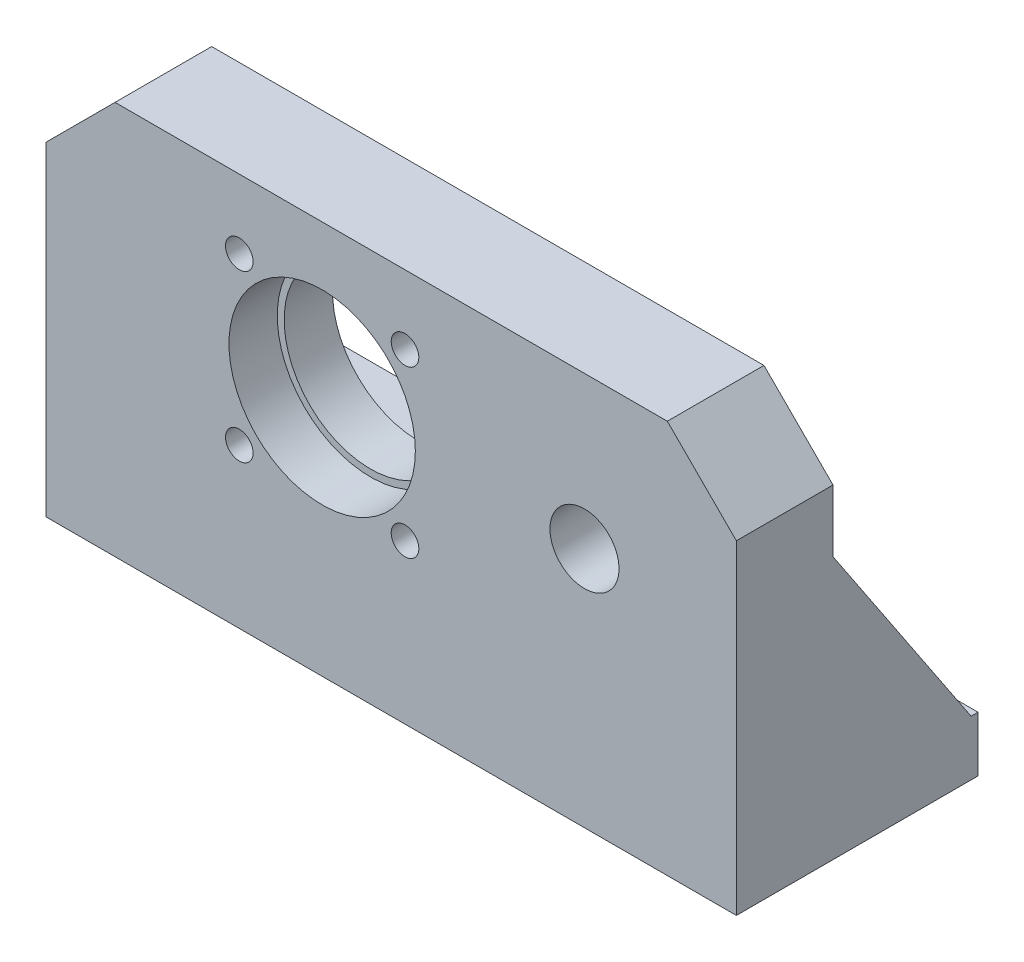
SolidWorks part; units mm, degrees
ref_plane "Front Plane" through (0, 0, 0) normal (0, 0, 1) x (1, 0, 0)
ref_plane "Top Plane" through (0, 0, 0) normal (0, 1, 0) x (1, 0, 0)
ref_plane "Right Plane" through (0, 0, 0) normal (1, 0, 0) x (0, 0, -1)
sketch "Sketch1" plane through (0, 0, 0) normal (0, 0, 1) x (1, 0, 0)
  line L0 (-40, -8) -> (-40, -35)
  line L1 (-40, -35) -> (60, -35)
  line L2 (60, -35) -> (60, 3.08)
  line L3 (60, 3.08) -> (60, 22)
  line L4 (60, 22) -> (-40, 22)
  line L5 (-40, 22) -> (-40, -8)
  circle A0 centre (0, 0) radius 13.5
  dimension "D1" = 27
  dimension "D2" = 100
  dimension "D3" = 35
  dimension "D4" = 57
  dimension "D5" = 60
extrude "Boss-Extrude1" add sketch "Sketch1" along normal blind 14
sketch "Sketch2" plane through (0, 0, 14) normal (0, 0, 1) x (1, 0, 0)
  circle A0 centre (0, 0) radius 13.5
  circle A1 centre (0, 0) radius 12.5
extrude "Boss-Extrude2" add sketch "Sketch2" against normal blind 7
sketch "Sketch11" plane through (0, 0, 14) normal (0, 0, 1) x (1, 0, 0)
  line L5 (-12, -12) -> (12, -12) construction
  line L6 (-12, -12) -> (-12, 12) construction
  line L7 (-12, 12) -> (12, 12) construction
  line L8 (12, -12) -> (12, 12) construction
  line L9 (-12, -12) -> (12, 12) construction
  line L10 (-12, 12) -> (12, -12) construction
  point P0 (0, 0)
sketch "Sketch16" plane through (0, -35, 0) normal (0, -1, 0) x (1, 0, 0)
  line L0 (60, 14) -> (60, 0) construction
  line L1 (-40, 0) -> (60, 0)
  line L2 (-40, 0) -> (-40, 35)
  line L3 (-40, 35) -> (60, 35)
  line L4 (60, 0) -> (60, 35)
  dimension "D1" = 35
extrude "Boss-Extrude3" add sketch "Sketch16" against normal blind 8
sketch "Sketch17" plane through (60, 0, 0) normal (1, 0, 0) x (0, 0, -1)
  line L0 (-34, -27) -> (-14, 3)
  line L1 (-14, -27) -> (-14, 22) construction
  line L2 (-34, -27) -> (-14, -27)
  line L3 (-14, -27) -> (-14, 3)
  line L5 (-14, -27) -> (-35, -27) construction
  dimension "D1" = 20
  dimension "D2" = 30
extrude "Boss-Extrude4" add sketch "Sketch17" against normal blind 8
ref_plane "Plane1" through (10, 0, 0) normal (1, 0, 0) x (0, 0, -1)
mirror "Mirror1" about plane through (10, 0, 0) normal (1, 0, 0) of "Boss-Extrude4"
sketch "Sketch19" plane through (0, 0, 35) normal (0, 0, 1) x (1, 0, 0)
  line L1 (60, -27) -> (16, -27)
  line L2 (60, -27) -> (60, 22)
  line L3 (60, 22) -> (16, 22)
  line L4 (16, -27) -> (16, 22)
  dimension "D1" = 44
sketch "Sketch20" plane through (0, 0, 0) normal (0, 0, -1) x (-1, 0, 0)
  line L5 (-12, -12) -> (12, -12) construction
  line L6 (-12, -12) -> (-12, 12) construction
  line L7 (-12, 12) -> (12, 12) construction
  line L8 (12, -12) -> (12, 12) construction
  line L9 (-12, -12) -> (12, 12) construction
  line L10 (-12, 12) -> (12, -12) construction
  point P0 (0, 0)
hole_wizard "Ø4.0mm Dowel Hole1" positions "Sketch23" profile "Sketch24" hole size "Ø4.0" standard "ISO"
sketch "Sketch23" plane through (0, 0, 0) normal (0, 0, -1) x (-1, 0, 0)
  point P0 (-12, 12)
  point P3 (12, 12)
  point P6 (12, -12)
  point P9 (-12, -12)
sketch "Sketch24" plane through (12, 12, 0) normal (1, 0, 0) x (0, 1, 0)
  line L0 (0, 0) -> (0, 11.2017)
  line L1 (0, 11.2017) -> (2, 10)
  line L2 (2, 10) -> (2, 0)
  line L5 (2, 0) -> (0, 0)
  line L10 (0, 11.2017) -> (-2, 10) construction
  line L11 (0, -6.35) -> (0, 107.95) construction
  dimension "Hole Dia." = 4
  dimension "Hole Depth" = 10
  dimension "Drill Angle" = 118
sketch "Sketch15" plane through (0, 0, 0) normal (0, 0, -1) x (-1, 0, 0)
  line L0 (-60, 0) -> (-38, 0) construction
  circle A0 centre (-38, 0) radius 5
  dimension "D2" = 0
  dimension "D1" = 22
extrude "Cut-Extrude1" cut sketch "Sketch15" against normal through all
mirror "Mirror2" about plane through (0, 0, 0) normal (0, 0, 1) of bodies 108
delete or keep bodies "Body-Delete/Keep 1" type delete bodies bodies 108
chamfer "Chamfer1" distance 10 angle 45 2 edges at (60, 22, -7) (-40, 22, -7)
